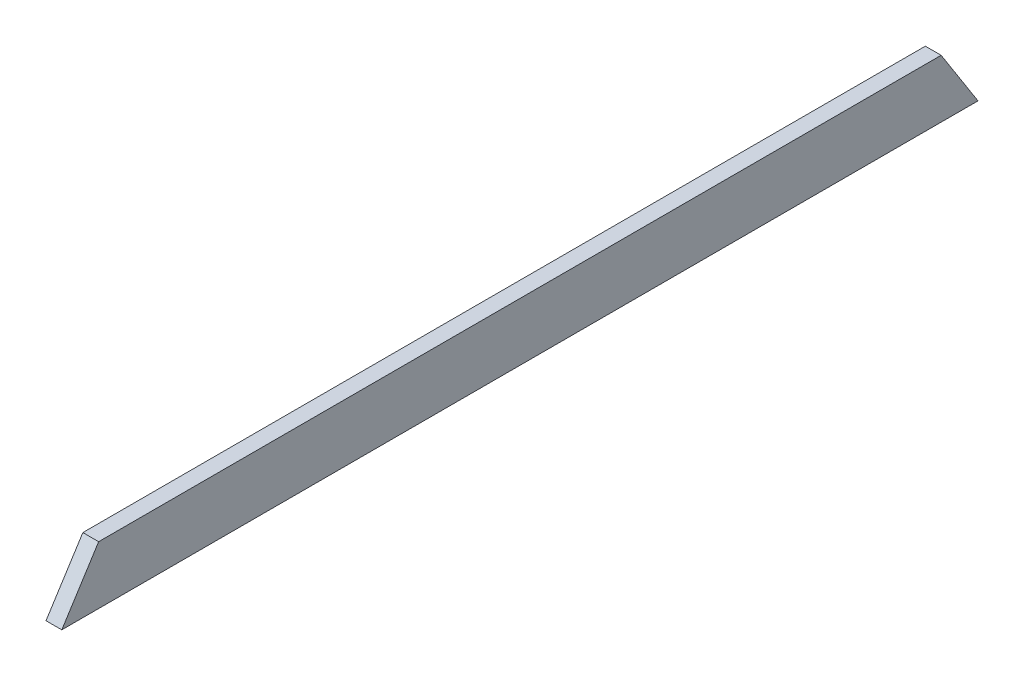
SolidWorks part; units mm, degrees
material "3.3320 (EN-AW 5019)"
ref_plane "Спереди" through (0, 0, 0) normal (0, 0, 1) x (1, 0, 0)
ref_plane "Сверху" through (0, 0, 0) normal (0, 1, 0) x (1, 0, 0)
ref_plane "Справа" through (0, 0, 0) normal (1, 0, 0) x (0, 0, -1)
sketch "Эскиз1" plane through (0, 0, 0) normal (1, 0, 0) x (0, 0, -1)
  line L0 (-87, 0) -> (87, 0)
  line L1 (87, 0) -> (80, 11)
  line L2 (80, 11) -> (-80, 11)
  line L3 (-80, 11) -> (-87, 0)
  dimension "D1" = 174
  dimension "D2" = 160
  dimension "D3" = 7
  dimension "D4" = 11
extrude "Бобышка-Вытянуть1" add sketch "Эскиз1" along normal blind 3
